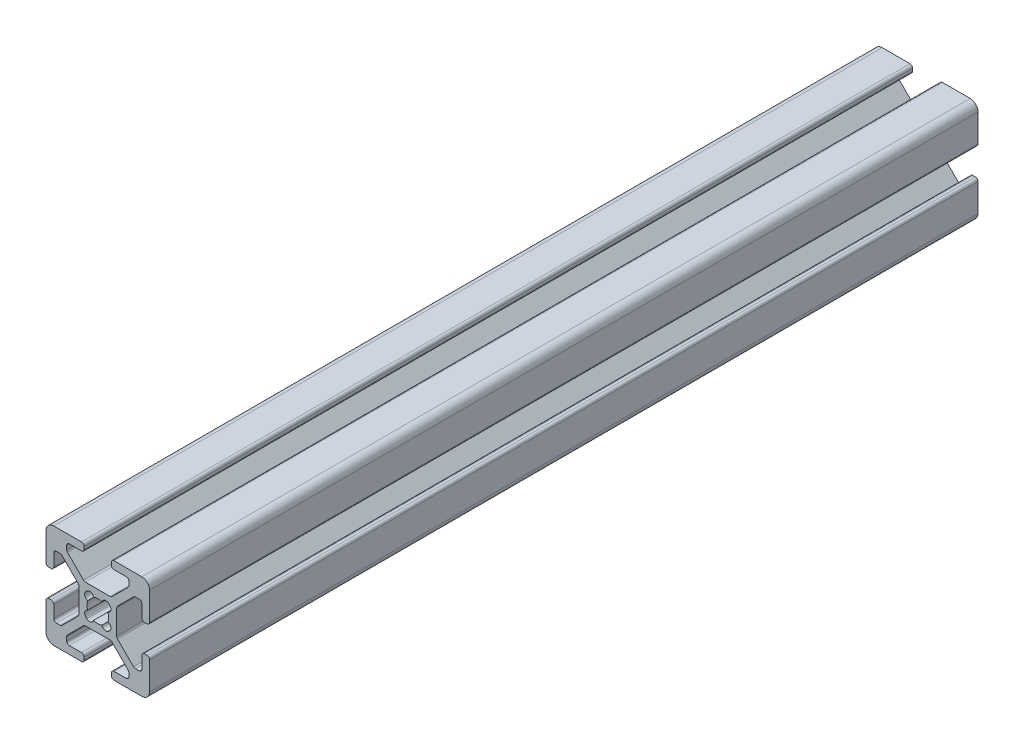
SolidWorks part; units mm, degrees
ref_plane "Front Plane" through (0, 0, 0) normal (0, 0, 1) x (1, 0, 0)
ref_plane "Top Plane" through (0, 0, 0) normal (0, 1, 0) x (1, 0, 0)
ref_plane "Right Plane" through (0, 0, 0) normal (1, 0, 0) x (0, 0, -1)
ref_plane "Plane1" through (0, 0, -160) normal (0, 0, -1) x (-1, 0, 0)
sketch "Sketch1" plane through (0, 0, -160) normal (0, 0, -1) x (-1, 0, 0)
  line L0 (10, -8.5) -> (10, -3.138)
  line L1 (9.492, -2.63) -> (9.008, -2.63)
  line L2 (8.5, -3.138) -> (8.5, -5.487)
  line L3 (7.992, -5.995) -> (7.2659, -5.995)
  line L4 (6.9067, -5.8462) -> (3.8038, -2.7433)
  line L5 (3.655, -2.3841) -> (3.655, 2.3838)
  line L6 (3.8038, 2.743) -> (6.907, 5.8462)
  line L7 (7.2662, 5.995) -> (7.992, 5.995)
  line L8 (8.5, 5.487) -> (8.5, 3.138)
  line L9 (9.008, 2.63) -> (9.492, 2.63)
  line L10 (10, 3.138) -> (10, 8.5)
  line L11 (8.5, 10) -> (3.138, 10)
  line L12 (2.63, 9.492) -> (2.63, 9.008)
  line L13 (3.138, 8.5) -> (5.487, 8.5)
  line L14 (5.995, 7.992) -> (5.995, 7.2659)
  line L15 (5.8462, 6.9067) -> (2.7433, 3.8038)
  line L16 (2.3841, 3.655) -> (-2.3838, 3.655)
  line L17 (-2.743, 3.8038) -> (-5.8462, 6.907)
  line L18 (-5.995, 7.2662) -> (-5.995, 7.992)
  line L19 (-5.487, 8.5) -> (-3.138, 8.5)
  line L20 (-2.63, 9.008) -> (-2.63, 9.492)
  line L21 (-3.138, 10) -> (-8.5, 10)
  line L22 (-10, 8.5) -> (-10, 3.138)
  line L23 (-9.492, 2.63) -> (-9.008, 2.63)
  line L24 (-8.5, 3.138) -> (-8.5, 5.487)
  line L25 (-7.992, 5.995) -> (-7.2659, 5.995)
  line L26 (-6.9067, 5.8462) -> (-3.8038, 2.7433)
  line L27 (-3.655, 2.3841) -> (-3.655, -2.3838)
  line L28 (-3.8038, -2.743) -> (-6.907, -5.8462)
  line L29 (-7.2662, -5.995) -> (-7.992, -5.995)
  line L30 (-8.5, -5.487) -> (-8.5, -3.138)
  line L31 (-9.008, -2.63) -> (-9.492, -2.63)
  line L32 (-10, -3.138) -> (-10, -8.5)
  line L33 (-8.5, -10) -> (-3.138, -10)
  line L34 (-2.63, -9.492) -> (-2.63, -9.008)
  line L35 (-3.138, -8.5) -> (-5.487, -8.5)
  line L36 (-5.995, -7.992) -> (-5.995, -7.2659)
  line L37 (-5.8462, -6.9067) -> (-2.7433, -3.8038)
  line L38 (-2.3841, -3.655) -> (2.3838, -3.655)
  line L39 (2.743, -3.8038) -> (5.8462, -6.907)
  line L40 (5.995, -7.2662) -> (5.995, -7.992)
  line L41 (5.487, -8.5) -> (3.138, -8.5)
  line L42 (2.63, -9.008) -> (2.63, -9.492)
  line L43 (3.138, -10) -> (8.5, -10)
  line L44 (2.3045, -2.1245) -> (2.1245, -2.3045)
  line L45 (-2.1245, -2.3045) -> (-2.3045, -2.1245)
  line L46 (-2.3045, 2.1245) -> (-2.1245, 2.3045)
  line L47 (2.1245, 2.3045) -> (2.3045, 2.1245)
  arc A0 (10, -3.138) -> (9.492, -2.63) centre (9.492, -3.138) ccw
  arc A1 (9.008, -2.63) -> (8.5, -3.138) centre (9.008, -3.138) ccw
  arc A2 (8.5, -5.487) -> (7.992, -5.995) centre (7.992, -5.487) cw
  arc A3 (7.2659, -5.995) -> (6.9067, -5.8462) centre (7.2659, -5.487) cw
  arc A4 (3.8038, -2.7433) -> (3.655, -2.3841) centre (4.163, -2.3841) cw
  arc A5 (3.655, 2.3838) -> (3.8038, 2.743) centre (4.163, 2.3838) cw
  arc A6 (6.907, 5.8462) -> (7.2662, 5.995) centre (7.2662, 5.487) cw
  arc A7 (7.992, 5.995) -> (8.5, 5.487) centre (7.992, 5.487) cw
  arc A8 (8.5, 3.138) -> (9.008, 2.63) centre (9.008, 3.138) ccw
  arc A9 (9.492, 2.63) -> (10, 3.138) centre (9.492, 3.138) ccw
  arc A10 (10, 8.5) -> (8.5, 10) centre (8.5, 8.5) ccw
  arc A11 (3.138, 10) -> (2.63, 9.492) centre (3.138, 9.492) ccw
  arc A12 (2.63, 9.008) -> (3.138, 8.5) centre (3.138, 9.008) ccw
  arc A13 (5.487, 8.5) -> (5.995, 7.992) centre (5.487, 7.992) cw
  arc A14 (5.995, 7.2659) -> (5.8462, 6.9067) centre (5.487, 7.2659) cw
  arc A15 (2.7433, 3.8038) -> (2.3841, 3.655) centre (2.3841, 4.163) cw
  arc A16 (-2.3838, 3.655) -> (-2.743, 3.8038) centre (-2.3838, 4.163) cw
  arc A17 (-5.8462, 6.907) -> (-5.995, 7.2662) centre (-5.487, 7.2662) cw
  arc A18 (-5.995, 7.992) -> (-5.487, 8.5) centre (-5.487, 7.992) cw
  arc A19 (-3.138, 8.5) -> (-2.63, 9.008) centre (-3.138, 9.008) ccw
  arc A20 (-2.63, 9.492) -> (-3.138, 10) centre (-3.138, 9.492) ccw
  arc A21 (-8.5, 10) -> (-10, 8.5) centre (-8.5, 8.5) ccw
  arc A22 (-10, 3.138) -> (-9.492, 2.63) centre (-9.492, 3.138) ccw
  arc A23 (-9.008, 2.63) -> (-8.5, 3.138) centre (-9.008, 3.138) ccw
  arc A24 (-8.5, 5.487) -> (-7.992, 5.995) centre (-7.992, 5.487) cw
  arc A25 (-7.2659, 5.995) -> (-6.9067, 5.8462) centre (-7.2659, 5.487) cw
  arc A26 (-3.8038, 2.7433) -> (-3.655, 2.3841) centre (-4.163, 2.3841) cw
  arc A27 (-3.655, -2.3838) -> (-3.8038, -2.743) centre (-4.163, -2.3838) cw
  arc A28 (-6.907, -5.8462) -> (-7.2662, -5.995) centre (-7.2662, -5.487) cw
  arc A29 (-7.992, -5.995) -> (-8.5, -5.487) centre (-7.992, -5.487) cw
  arc A30 (-8.5, -3.138) -> (-9.008, -2.63) centre (-9.008, -3.138) ccw
  arc A31 (-9.492, -2.63) -> (-10, -3.138) centre (-9.492, -3.138) ccw
  arc A32 (-10, -8.5) -> (-8.5, -10) centre (-8.5, -8.5) ccw
  arc A33 (-3.138, -10) -> (-2.63, -9.492) centre (-3.138, -9.492) ccw
  arc A34 (-2.63, -9.008) -> (-3.138, -8.5) centre (-3.138, -9.008) ccw
  arc A35 (-5.487, -8.5) -> (-5.995, -7.992) centre (-5.487, -7.992) cw
  arc A36 (-5.995, -7.2659) -> (-5.8462, -6.9067) centre (-5.487, -7.2659) cw
  arc A37 (-2.7433, -3.8038) -> (-2.3841, -3.655) centre (-2.3841, -4.163) cw
  arc A38 (2.3838, -3.655) -> (2.743, -3.8038) centre (2.3838, -4.163) cw
  arc A39 (5.8462, -6.907) -> (5.995, -7.2662) centre (5.487, -7.2662) cw
  arc A40 (5.995, -7.992) -> (5.487, -8.5) centre (5.487, -7.992) cw
  arc A41 (3.138, -8.5) -> (2.63, -9.008) centre (3.138, -9.008) ccw
  arc A42 (2.63, -9.492) -> (3.138, -10) centre (3.138, -9.492) ccw
  arc A43 (8.5, -10) -> (10, -8.5) centre (8.5, -8.5) ccw
  arc A44 (1.9358, 0.8037) -> (1.9358, -0.8037) centre (0, 0) cw
  arc A45 (1.9358, -0.8037) -> (2.3045, -2.1245) centre (1.748, -1.568) cw
  arc A46 (2.1245, -2.3045) -> (0.8037, -1.9358) centre (1.568, -1.748) cw
  arc A47 (0.8037, -1.9358) -> (-0.8037, -1.9358) centre (0, 0) cw
  arc A48 (-0.8037, -1.9358) -> (-2.1245, -2.3045) centre (-1.568, -1.748) cw
  arc A49 (-2.3045, -2.1245) -> (-1.9358, -0.8037) centre (-1.748, -1.568) cw
  arc A50 (-1.9358, -0.8037) -> (-1.9358, 0.8037) centre (0, 0) cw
  arc A51 (-1.9358, 0.8037) -> (-2.3045, 2.1245) centre (-1.748, 1.568) cw
  arc A52 (-2.1245, 2.3045) -> (-0.8037, 1.9358) centre (-1.568, 1.748) cw
  arc A53 (-0.8037, 1.9358) -> (0.8037, 1.9358) centre (0, 0) cw
  arc A54 (0.8037, 1.9358) -> (2.1245, 2.3045) centre (1.568, 1.748) cw
  arc A55 (2.3045, 2.1245) -> (1.9358, 0.8037) centre (1.748, 1.568) cw
extrude "Boss-Extrude1" add sketch "Sketch1" against normal blind 160
